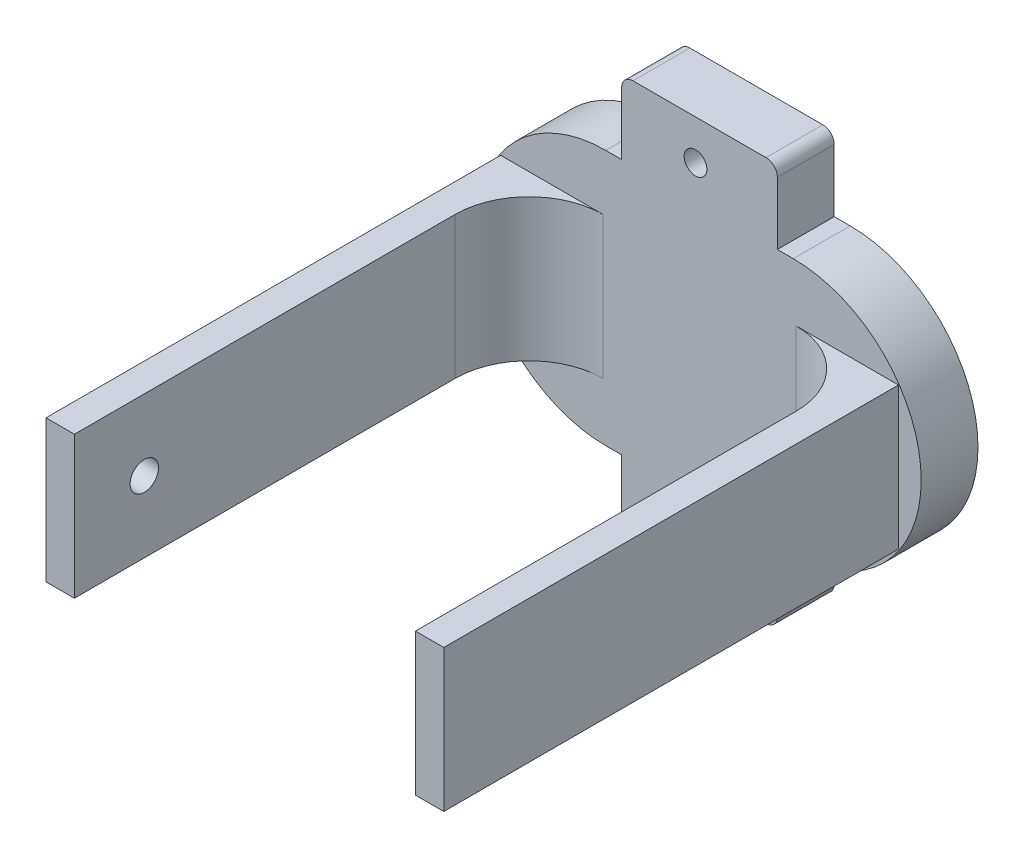
SolidWorks part; units mm, degrees
ref_plane "前基準面" through (0, 0, 0) normal (0, 0, 1) x (1, 0, 0)
ref_plane "上基準面" through (0, 0, 0) normal (0, 1, 0) x (1, 0, 0)
ref_plane "右基準面" through (0, 0, 0) normal (1, 0, 0) x (0, 0, -1)
sketch "草圖1" plane through (0, 0, 0) normal (0, 0, 1) x (1, 0, 0)
  line L0 (-12.8672, 10.489) -> (20.1328, 10.489) construction
  line L1 (-12.8672, 32.989) -> (20.1328, 32.989)
  line L2 (-12.8672, -12.011) -> (20.1328, -12.011)
  line L4 (-10.0672, 32.989) -> (17.3328, 32.989)
  line L5 (-10.0672, 32.989) -> (-10.0672, 43.989)
  line L6 (-8.0672, 45.989) -> (15.3328, 45.989)
  line L7 (17.3328, 32.989) -> (17.3328, 43.989)
  line L8 (-10.0672, -12.011) -> (17.3328, -12.011)
  line L9 (-10.0672, -12.011) -> (-10.0672, -23.011)
  line L10 (-8.0672, -25.011) -> (15.3328, -25.011)
  line L11 (17.3328, -12.011) -> (17.3328, -23.011)
  arc A0 (-12.8672, 32.989) -> (-12.8672, -12.011) centre (-12.8672, 10.489) ccw
  arc A1 (20.1328, -12.011) -> (20.1328, 32.989) centre (20.1328, 10.489) ccw
  circle A2 centre (2.9215, 38.989) radius 2
  circle A3 centre (2.9215, -18.011) radius 2
  arc A4 (15.3328, -25.011) -> (17.3328, -23.011) centre (15.3328, -23.011) ccw
  arc A5 (-8.0672, -25.011) -> (-10.0672, -23.011) centre (-8.0672, -23.011) cw
  arc A6 (17.3328, 43.989) -> (15.3328, 45.989) centre (15.3328, 43.989) ccw
  arc A7 (-8.0672, 45.989) -> (-10.0672, 43.989) centre (-8.0672, 43.989) ccw
  point P2 (3.6328, 10.489)
  point P21 (17.3328, -25.011)
  point P24 (-10.0672, -25.011)
  point P27 (17.3328, 45.989)
  point P30 (-10.0672, 45.989)
  dimension "D9" = 4
  dimension "D10" = 6
  dimension "D11" = 6
  dimension "D12" = 4
  dimension "D13" = 2
  dimension "D1" = 33
  dimension "D2" = 45
  dimension "D3" = 27.4
  dimension "D4" = 13
  dimension "D5" = 2.8
  dimension "D6" = 13
  dimension "D7" = 2.8
  dimension "D8" = 27.4
extrude "填料-伸長1" add sketch "草圖1" along normal blind 10
sketch "草圖2" plane through (0, 0, 10) normal (0, 0, 1) x (1, 0, 0)
  line L0 (17.3328, -12.011) -> (20.1328, -12.011) construction
  line L1 (-31.3672, 22.989) -> (38.6328, 22.989)
  line L2 (-31.3672, 22.989) -> (-31.3672, -2.011)
  line L3 (-31.3672, -2.011) -> (38.6328, -2.011)
  line L4 (38.6328, 22.989) -> (38.6328, -2.011)
  line L6 (-26.3672, 22.989) -> (33.6328, 22.989)
  line L7 (-26.3672, 22.989) -> (-26.3672, -2.011)
  line L8 (-26.3672, -2.011) -> (33.6328, -2.011)
  line L9 (33.6328, 22.989) -> (33.6328, -2.011)
  arc A0 (20.1328, -12.011) -> (20.1328, 32.989) centre (20.1328, 10.489) ccw construction
  point P13 (0, 0)
  dimension "D1" = 18.5
  dimension "D2" = 70
  dimension "D3" = 25
  dimension "D4" = 10
  dimension "D5" = 25
  dimension "D6" = 60
  dimension "D7" = 5
extrude "填料-伸長2" add sketch "草圖2" along normal blind 80 contours L7 L1 L2 L3 | L1 L9 L3 L4
sketch "草圖6" plane through (0, -2.011, 0) normal (0, -1, 0) x (1, 0, 0)
  line L1 (-26.3672, 25) -> (-11.3672, 25)
  line L2 (-26.3672, 25) -> (-26.3672, 23)
  line L3 (-13.3672, 10) -> (-11.3672, 10)
  line L4 (-11.3672, 25) -> (-11.3672, 10)
  line L9 (-26.3672, 90) -> (-26.3672, 10) construction
  line L11 (-26.3672, 25) -> (-13.3672, 25)
  line L12 (-26.3672, 25) -> (-26.3672, 10)
  line L13 (-26.3672, 10) -> (-13.3672, 10)
  line L14 (-13.3672, 25) -> (-13.3672, 10)
  arc A0 (-13.3672, 10) -> (-26.3672, 23) centre (-13.3672, 23) cw
  point P10 (-26.3672, 10)
  line M6 (-26.3672, 10) -> (-26.3672, 90)
  dimension "D3" = 13
  dimension "D1" = 15
  dimension "D2" = 15
extrude "填料-伸長3" add sketch "草圖6" against normal blind 25 contours L13 A0 M6
sketch "草圖7" plane through (0, -2.011, 0) normal (0, -1, 0) x (1, 0, 0)
  line L1 (20.6328, 10) -> (18.6328, 10)
  line L2 (33.6328, 23) -> (33.6328, 25)
  line L3 (33.6328, 25) -> (18.6328, 25)
  line L4 (18.6328, 10) -> (18.6328, 25)
  line L5 (33.6328, 23) -> (20.6328, 23)
  line L6 (33.6328, 23) -> (33.6328, 10)
  line L7 (33.6328, 10) -> (20.6328, 10)
  line L8 (20.6328, 23) -> (20.6328, 10)
  arc A0 (33.6328, 23) -> (20.6328, 10) centre (20.6328, 23) cw
  point P7 (33.6328, 10)
  line M7 (33.6328, 90) -> (33.6328, 10)
  dimension "D3" = 13
  dimension "D1" = 15
  dimension "D2" = 15
extrude "填料-伸長4" add sketch "草圖7" against normal blind 25 contours A0 L7 M7
sketch "草圖8" plane through (-26.3672, 0, 0) normal (1, 0, 0) x (0, 0, -1)
  line L0 (-90, 22.989) -> (-90, -2.011) construction
  line L1 (-90, 22.989) -> (-23, 22.989) construction
  circle A0 centre (-77.7, 10.489) radius 2.5
  dimension "D1" = 5
  dimension "D3" = 12.5
  dimension "D2" = 12.3
extrude "除料-伸長1" cut sketch "草圖8" against normal up to next
